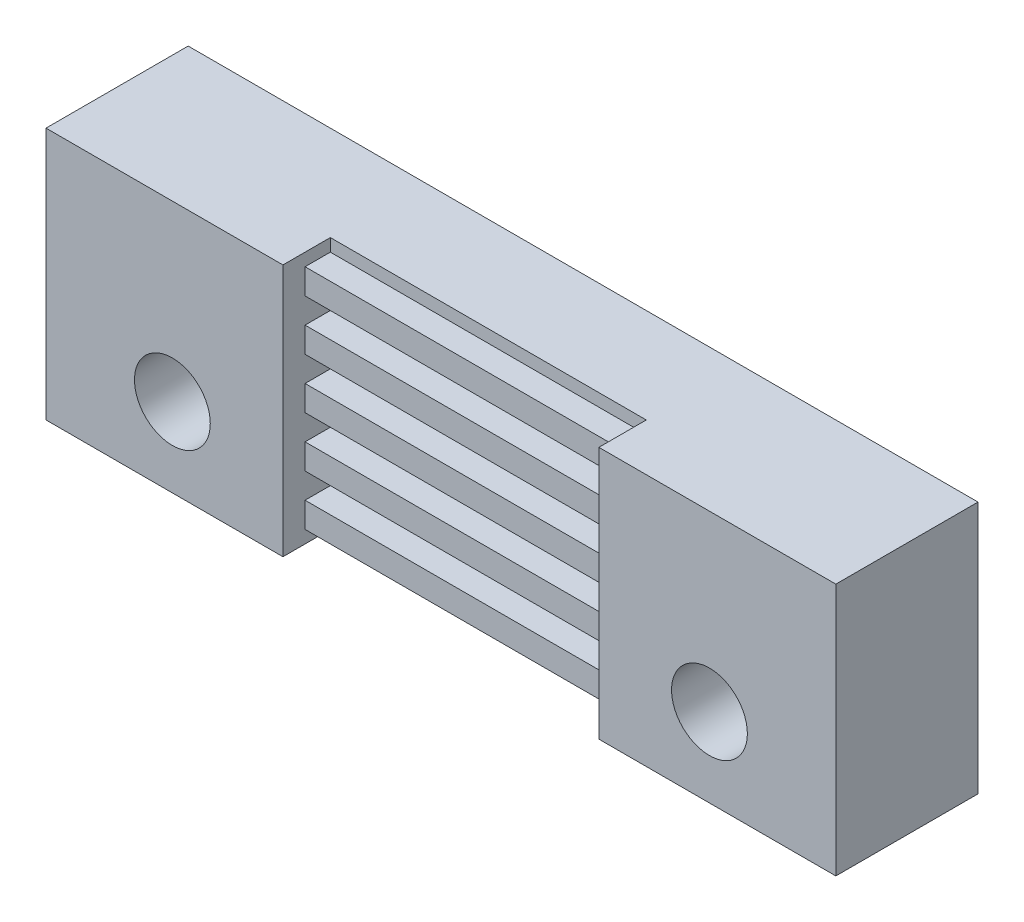
SolidWorks part; units mm, degrees
ref_plane "前视基准面" through (0, 0, 0) normal (0, 0, 1) x (1, 0, 0)
ref_plane "上视基准面" through (0, 0, 0) normal (0, 1, 0) x (1, 0, 0)
ref_plane "右视基准面" through (0, 0, 0) normal (1, 0, 0) x (0, 0, -1)
other "Configuration Table"
sketch "草图1" plane through (0, 0, 0) normal (0, 0, 1) x (1, 0, 0)
  line L0 (-12.3902, -4.5489) -> (12.6098, -4.5489)
  line L1 (12.6098, -4.5489) -> (12.6098, 3.4511)
  line L2 (12.6098, 3.4511) -> (-12.3902, 3.4511)
  line L3 (-12.3902, 3.4511) -> (-12.3902, -4.5489)
  circle A0 centre (-8.3902, -2.0489) radius 1.2
  circle A1 centre (8.6098, -2.0489) radius 1.2
extrude "凸台-拉伸2" add sketch "草图1" along normal blind 4
sketch "草图2" plane through (0, 0, 4) normal (0, 0, 1) x (1, 0, 0)
  line L1 (-12.3902, -4.5489) -> (12.6098, -4.5489) construction
  line L3 (-4.8902, -4.1489) -> (-4.8902, -3.3489)
  line L8 (-4.8902, -4.1489) -> (5.1098, -4.1489)
  line L9 (5.1098, -4.1489) -> (5.1098, -3.3489)
  line L10 (5.1098, -3.3489) -> (-4.8902, -3.3489)
  line L12 (-4.8902, -2.5489) -> (5.1098, -2.5489)
  line L13 (5.1098, -2.5489) -> (5.1098, -1.7489)
  line L14 (5.1098, -1.7489) -> (-4.8902, -1.7489)
  line L15 (5.1098, -1.7489) -> (5.1098, -2.5489)
  line L16 (-4.8902, -0.9489) -> (5.1098, -0.9489)
  line L17 (-4.8902, 2.2511) -> (5.1098, 2.2511)
  line L18 (5.1098, 1.4511) -> (-4.8902, 1.4511)
  line L19 (-4.8902, 0.6511) -> (5.1098, 0.6511)
  line L20 (5.1098, -0.1489) -> (-4.8902, -0.1489)
  line L22 (5.1098, 1.4511) -> (5.1098, 0.6511)
  line L23 (-4.8902, 0.6511) -> (-4.8902, 1.4511)
  line L24 (5.1098, -0.1489) -> (5.1098, -0.9489)
  line L25 (-4.8902, -0.9489) -> (-4.8902, -0.1489)
  line L26 (-4.8902, -2.5489) -> (-4.8902, -1.7489)
  line L27 (5.1098, -3.3489) -> (5.1098, -4.1489)
  line L28 (-4.8902, 2.2511) -> (-4.8902, 3.0511)
  line L29 (-4.8902, 3.0511) -> (5.1098, 3.0511)
  line L30 (5.1098, 3.0511) -> (5.1098, 2.2511)
  dimension "D1" = 0.4
extrude "凸台-拉伸3" add sketch "草图2" along normal blind 0.8
sketch "草图3" plane through (0, 0, 4) normal (0, 0, 1) x (1, 0, 0)
  line L0 (-12.3902, -4.5489) -> (12.6098, -4.5489) construction
  line L1 (-12.3902, 3.4511) -> (-4.8902, 3.4511)
  line L2 (-12.3902, 3.4511) -> (-12.3902, -4.5489)
  line L3 (-12.3902, -4.5489) -> (-4.8902, -4.5489)
  line L4 (-4.8902, 3.4511) -> (-4.8902, -4.5489)
  line L6 (12.6098, 3.4511) -> (5.1098, 3.4511)
  line L7 (12.6098, 3.4511) -> (12.6098, -4.5489)
  line L8 (12.6098, -4.5489) -> (5.1098, -4.5489)
  line L9 (5.1098, 3.4511) -> (5.1098, -4.5489)
  circle A0 centre (-8.3902, -2.0489) radius 1.2
  circle A1 centre (8.6098, -2.0489) radius 1.2
extrude "凸台-拉伸4" add sketch "草图3" along normal blind 1.5
sketch "草图4" plane through (0, 3.4511, 0) normal (0, 1, 0) x (1, 0, 0)
  line L0 (-12.3902, 0) -> (-12.3902, -1)
  line L1 (-12.3902, -5.5) -> (-12.3902, 0) construction
  line L2 (-12.3902, -1) -> (12.6098, -1)
  line L3 (12.6098, -5.5) -> (12.6098, 0) construction
  line L4 (12.6098, -1) -> (12.6098, 0)
  line L5 (12.6098, 0) -> (-12.3902, 0)
extrude "切除-拉伸1" cut sketch "草图4" against normal blind 19.5
